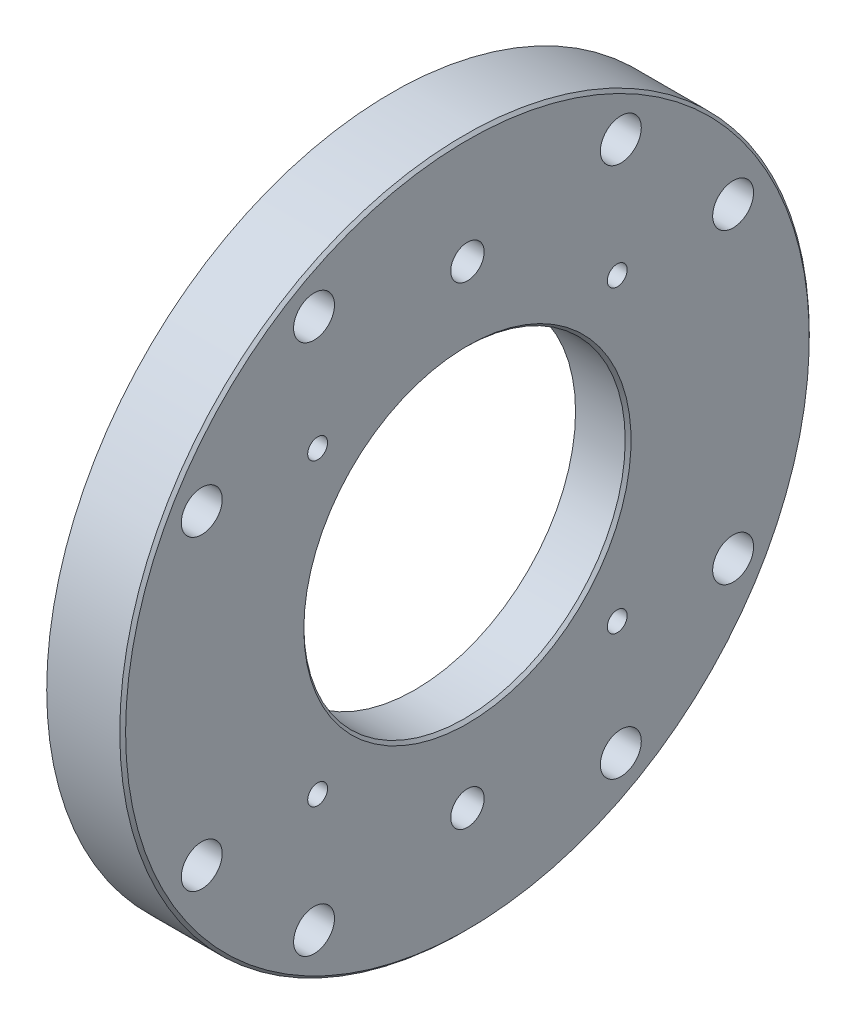
SolidWorks part; units mm, degrees
ref_plane "正面" through (0, 0, 0) normal (0, 0, 1) x (1, 0, 0)
ref_plane "平面" through (0, 0, 0) normal (0, 1, 0) x (1, 0, 0)
ref_plane "右側面" through (0, 0, 0) normal (1, 0, 0) x (0, 0, -1)
sketch "ｽｹｯﾁ1" plane through (0, 0, 0) normal (0, 0, 1) x (1, 0, 0)
  line L0 (0, 115.5) -> (0.5, 115)
  line L1 (0.5, 115) -> (3, 115)
  line L2 (3, 115) -> (3, 88)
  line L3 (3, 88) -> (8, 88)
  line L4 (8, 88) -> (8, 55)
  line L5 (8, 55) -> (25, 55)
  line L6 (25, 55) -> (26, 56)
  line L7 (26, 56) -> (26, 117)
  line L8 (26, 117) -> (25, 118)
  line L9 (25, 118) -> (0, 118)
  line L10 (0, 118) -> (0, 115.5)
  line L11 (0, 0) -> (26, 0) construction
revolve "回転1" add sketch "ｽｹｯﾁ1" angle 360 about L11
sketch "ｽｹｯﾁ2" plane through (0, 0, 0) normal (1, 0, 0) x (0, 0, -1)
  circle A0 centre (90.9327, 52.5) radius 7
  circle A1 centre (52.5, 90.9327) radius 7
  circle A2 centre (-52.5, 90.9327) radius 7
  circle A3 centre (-90.9327, 52.5) radius 7
  circle A4 centre (-90.9327, -52.5) radius 7
  circle A5 centre (-52.5, -90.9327) radius 7
  circle A6 centre (52.5, -90.9327) radius 7
  circle A7 centre (90.9327, -52.5) radius 7
  circle A8 centre (51.2652, 51.2652) radius 3.4
  circle A9 centre (-51.2652, 51.2652) radius 3.4
  circle A10 centre (-51.2652, -51.2652) radius 3.4
  circle A11 centre (51.2652, -51.2652) radius 3.4
  circle A12 centre (0, 81) radius 5.7226
  circle A13 centre (0, -81) radius 5.7226
extrude "ｶｯﾄ - 押し出し1" cut sketch "ｽｹｯﾁ2" against normal through all and the other way through all
